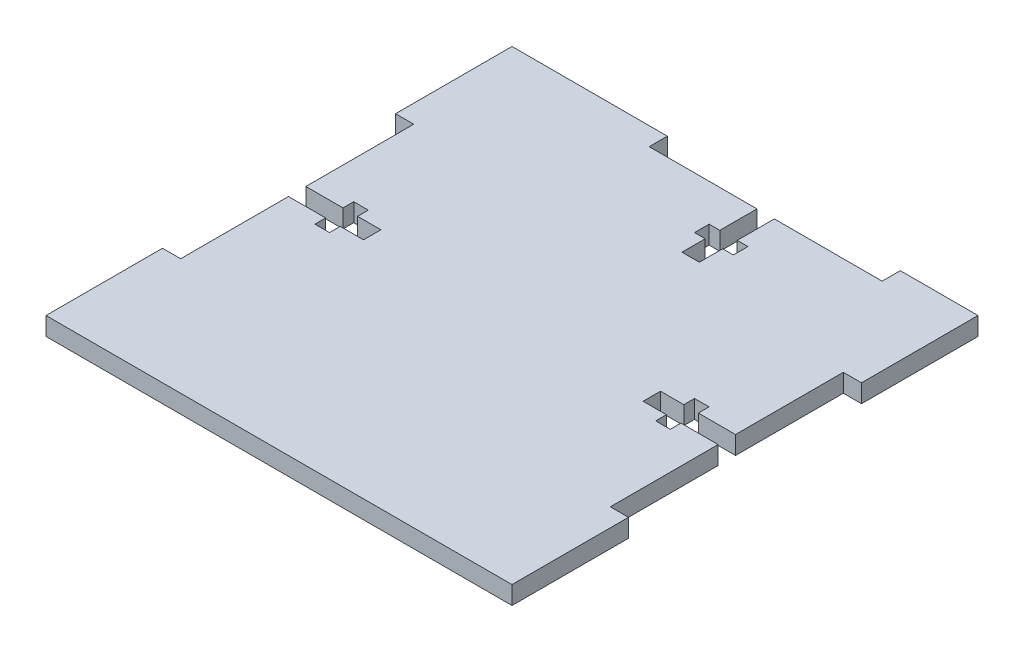
SolidWorks part; units mm, degrees
ref_plane "Front Plane" through (0, 0, 0) normal (0, 0, 1) x (1, 0, 0)
ref_plane "Top Plane" through (0, 0, 0) normal (0, 1, 0) x (1, 0, 0)
ref_plane "Right Plane" through (0, 0, 0) normal (1, 0, 0) x (0, 0, -1)
sketch "Sketch1" plane through (0, 0, 0) normal (0, 1, 0) x (1, 0, 0)
  line L1 (-38.1, -38.1) -> (38.1, -38.1)
  line L2 (-38.1, -38.1) -> (-38.1, 38.1)
  line L3 (-38.1, 38.1) -> (38.1, 38.1)
  line L4 (38.1, -38.1) -> (38.1, 38.1)
  line L5 (-38.1, -38.1) -> (38.1, 38.1) construction
  line L6 (-38.1, 38.1) -> (38.1, -38.1) construction
  point P0 (0, 0)
  dimension "D1" = 76.2
  dimension "D2" = 76.2
extrude "Boss-Extrude1" add sketch "Sketch1" along normal blind 2.9718
sketch "Sketch2" plane through (0, 2.9718, 0) normal (0, 1, 0) x (1, 0, 0)
  line L0 (-38.1, 0) -> (38.1, 0) construction
  line L1 (-38.1, 38.1) -> (-38.1, -38.1) construction
  line L2 (38.1, -38.1) -> (38.1, 38.1) construction
  line L8 (35.1282, -19.05) -> (38.1, -19.05)
  line L9 (35.1282, -19.05) -> (35.1282, 19.05)
  line L10 (35.1282, 19.05) -> (38.1, 19.05)
  line L11 (38.1, -19.05) -> (38.1, 19.05)
  line L12 (35.1282, -19.05) -> (38.1, 19.05) construction
  line L13 (35.1282, 19.05) -> (38.1, -19.05) construction
  point P6 (36.6141, 0)
  dimension "D1" = 38.1
  dimension "D2" = 2.9718
extrude "Cut-Extrude1" cut sketch "Sketch2" against normal through all
sketch "Sketch7" plane through (0, 2.9718, 0) normal (0, 1, 0) x (1, 0, 0)
  line L0 (-38.1, 0) -> (35.1282, 0) construction
  line L1 (-38.1, 38.1) -> (-38.1, -38.1) construction
  line L2 (35.1282, 19.05) -> (35.1282, -19.05) construction
  line L8 (35.1282, 1.4224) -> (29.0512, 1.4224)
  line L9 (29.0512, 1.4224) -> (29.0512, 3.175)
  line L14 (29.0512, 3.175) -> (26.67, 3.175)
  line L15 (26.67, 3.175) -> (26.67, 1.4224)
  line L16 (26.67, 1.4224) -> (22.86, 1.4224)
  line L17 (22.86, 1.4224) -> (22.86, -1.4224)
  line L18 (22.86, -1.4224) -> (26.67, -1.4224)
  line L19 (26.67, -1.4224) -> (26.67, -3.175)
  line L20 (26.67, -3.175) -> (29.0512, -3.175)
  line L21 (29.0512, -3.175) -> (29.0512, -1.4224)
  line L22 (29.0512, -1.4224) -> (35.1282, -1.4224)
  line L23 (35.1282, 1.4224) -> (35.1282, -1.4224)
  line L24 (38.1, 19.05) -> (38.1, 38.1) construction
  point P17 (22.86, 0)
  dimension "D1" = 2.8448
  dimension "D2" = 2.3813
  dimension "D3" = 6.35
  dimension "D4" = 3.175
  dimension "D5" = 15.24
  dimension "D6" = 3.81
extrude "Cut-Extrude7" cut sketch "Sketch7" against normal through all
sketch "Sketch8" plane through (0, 2.9718, 0) normal (0, 1, 0) x (1, 0, 0)
  line L0 (38.1, 38.1) -> (-38.1, 38.1) construction
  line L1 (-12.7, 38.1) -> (25.4, 38.1)
  line L2 (-12.7, 38.1) -> (-12.7, 35.1282)
  line L3 (-12.7, 35.1282) -> (25.4, 35.1282)
  line L4 (25.4, 38.1) -> (25.4, 35.1282)
  line L5 (6.35, 35.1282) -> (6.35, 38.1) construction
  line L6 (38.1, 19.05) -> (38.1, 38.1) construction
  line L8 (4.9276, 22.86) -> (7.7724, 22.86)
  line L9 (4.9276, 22.86) -> (4.9276, 35.1282)
  line L10 (4.9276, 35.1282) -> (7.7724, 35.1282)
  line L11 (7.7724, 22.86) -> (7.7724, 35.1282)
  line L12 (4.9276, 22.86) -> (7.7724, 35.1282) construction
  line L13 (4.9276, 35.1282) -> (7.7724, 22.86) construction
  line L14 (4.9276, 29.0513) -> (3.175, 29.0513)
  line L15 (4.9276, 29.0513) -> (4.9276, 26.67)
  line L16 (4.9276, 26.67) -> (3.175, 26.67)
  line L17 (3.175, 29.0513) -> (3.175, 26.67)
  line L18 (7.7724, 29.0513) -> (9.525, 29.0513)
  line L19 (7.7724, 29.0513) -> (7.7724, 26.67)
  line L20 (7.7724, 26.67) -> (9.525, 26.67)
  line L21 (9.525, 29.0513) -> (9.525, 26.67)
  point P10 (6.35, 28.9941)
  line M31 (38.1, 38.1) -> (-38.1, 38.1)
  dimension "D1" = 31.75
  dimension "D2" = 2.9718
  dimension "D3" = 38.1
  dimension "D4" = 2.8448
  dimension "D5" = 15.24
  dimension "D6" = 3.175
  dimension "D7" = 6.35
  dimension "D8" = 2.3813
  dimension "D9" = 3.81
extrude "Cut-Extrude8" cut sketch "Sketch8" against normal through all contours L4 L2 L3 M31 | L8 L11 L3 L9 | L21 L18 L11 L20 | L14 L17 L16 L15
mirror "Mirror1" about plane through (0, 0, 0) normal (1, 0, 0) of "Cut-Extrude1", "Cut-Extrude7"
